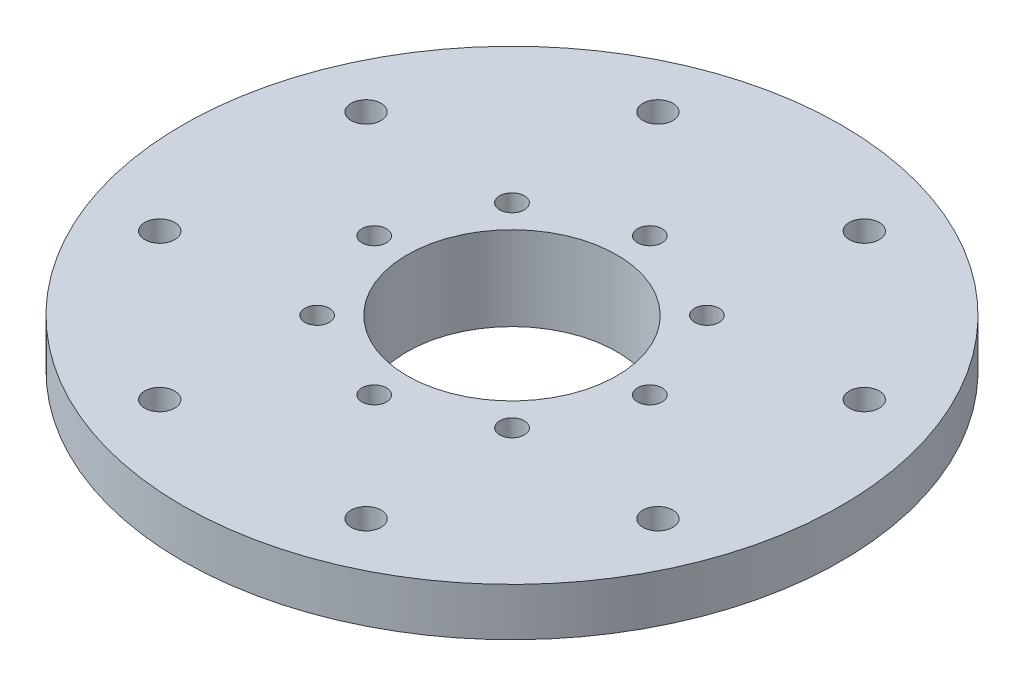
SolidWorks part; units mm, degrees
ref_plane "Front Plane" through (0, 0, 0) normal (0, 0, 1) x (1, 0, 0)
ref_plane "Top Plane" through (0, 0, 0) normal (0, 1, 0) x (1, 0, 0)
ref_plane "Right Plane" through (0, 0, 0) normal (1, 0, 0) x (0, 0, -1)
sketch "Sketch1" plane through (0, 0, 0) normal (0, 1, 0) x (1, 0, 0)
  circle A0 centre (0, 0) radius 55
  dimension "D1" = 110
extrude "Boss-Extrude1" add sketch "Sketch1" along normal blind 8
sketch "Sketch2" plane through (0, 0, 0) normal (0, -1, 0) x (1, 0, 0)
  circle A0 centre (0, 0) radius 27
  dimension "D1" = 54
extrude "Boss-Extrude2" add sketch "Sketch2" along normal blind 6
sketch "Sketch3" plane through (0, 8, 0) normal (0, 1, 0) x (1, 0, 0)
  circle A0 centre (0, 0) radius 17.5
  dimension "D1" = 35
extrude "Cut-Extrude1" cut sketch "Sketch3" against normal through all
sketch "Sketch4" plane through (0, 8, 0) normal (0, 1, 0) x (1, 0, 0)
  point P0 (0, 23)
  dimension "D1" = 23
hole_wizard "M4 Clearance Hole1" positions "Sketch4" profile "Sketch5" hole size "M4" standard "ANSI Metric" end condition through all
sketch "Sketch5" plane through (0, 8, -23) normal (1, 0, 0) x (0, 0, 1)
  line L0 (0, 0) -> (0, 14)
  line L1 (0, 14) -> (2.05, 14)
  line L2 (2.05, 14) -> (2.05, 0)
  line L5 (2.05, 0) -> (0, 0)
  line L11 (0, -6.35) -> (0, 107.95) construction
  dimension "Thru Hole Dia." = 4.1
  dimension "Thru Hole Depth" = 14
pattern_circular "CirPattern1" count 8 over 360 about axis through (0, 0, 0) along (0, 1, 0) of "M4 Clearance Hole1"
sketch "Sketch6" plane through (0, 8, 0) normal (0, 1, 0) x (1, 0, 0)
  line L0 (0, 0) -> (0, 55) construction
  line L1 (0, 0) -> (21.0476, 50.8134) construction
  circle A0 centre (0, 0) radius 55 construction
  point P6 (17.2208, 41.5746)
  dimension "D1" = 22.5
  dimension "D2" = 45
hole_wizard "Tap Drill for M6x1.0 Tap1" positions "Sketch6" profile "Sketch7" hole size "M6x1.0" standard "ANSI Metric" end condition through all
sketch "Sketch7" plane through (17.2208, 8, -41.5746) normal (1, 0, 0) x (0, 0, 1)
  line L0 (0, 0) -> (0, 14)
  line L1 (0, 14) -> (2.5, 14)
  line L2 (2.5, 14) -> (2.5, 0)
  line L5 (2.5, 0) -> (0, 0)
  line L11 (0, -6.35) -> (0, 107.95) construction
  dimension "Thru Hole Dia." = 5
  dimension "Thru Hole Depth" = 14
pattern_circular "CirPattern2" count 8 over 360 about axis through (0, 0, 0) along (0, 1, 0) of "Tap Drill for M6x1.0 Tap1"
equation "\"D1@Sketch6\" = 45 / 2"
